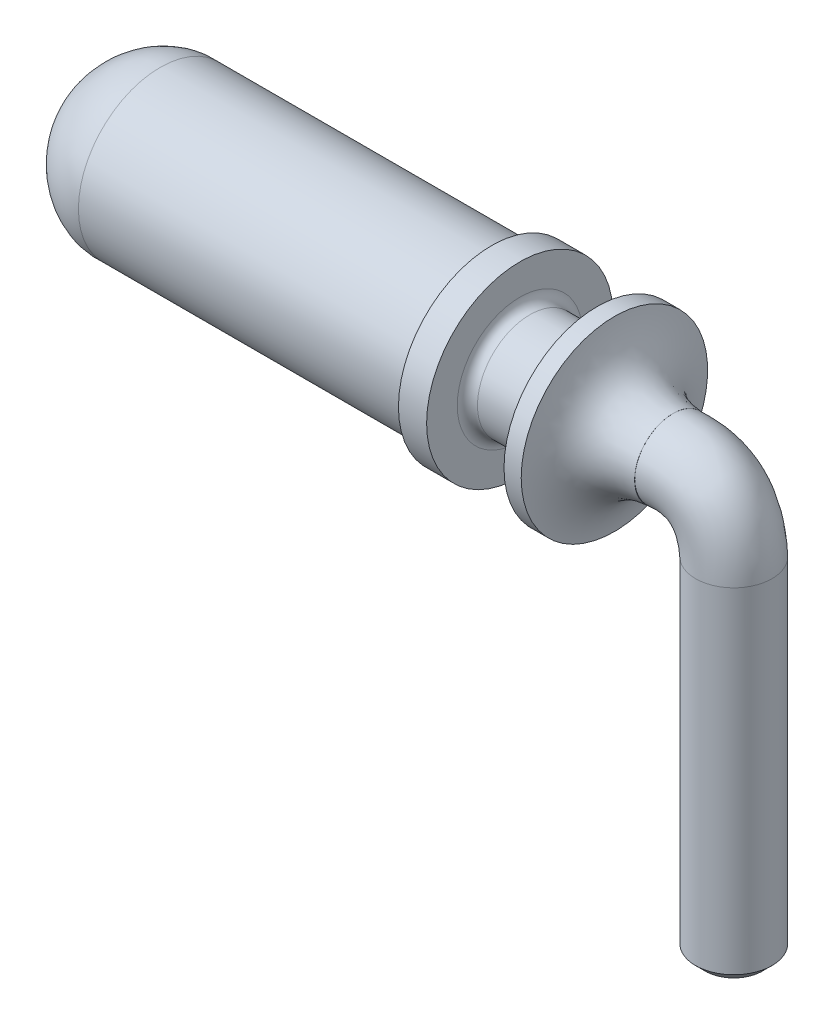
SolidWorks part; units mm, degrees
ref_plane "Front Plane" through (0, 0, 0) normal (0, 0, 1) x (1, 0, 0)
ref_plane "Top Plane" through (0, 0, 0) normal (0, 1, 0) x (1, 0, 0)
ref_plane "Right Plane" through (0, 0, 0) normal (1, 0, 0) x (0, 0, -1)
sketch "Sketch1" plane through (0, 0, 0) normal (0, 0, 1) x (1, 0, 0)
  line L0 (1.6261, 4.9868) -> (10.9215, 4.9868)
  line L1 (10.9215, 4.9868) -> (10.9215, 5.5888)
  line L2 (2.8612, 6.273) -> (8.0721, 6.273)
  line L3 (8.0721, 6.273) -> (8.0721, 6.4526)
  line L4 (8.0721, 6.4526) -> (8.5152, 6.4526)
  line L5 (8.5152, 6.4526) -> (8.5152, 5.9706)
  line L6 (8.6739, 5.8119) -> (9.5851, 5.8119)
  line L7 (9.732, 5.9589) -> (9.732, 6.4526)
  line L8 (9.732, 6.4526) -> (10.0024, 6.4526)
  arc A0 (8.5152, 5.9706) -> (8.6739, 5.8119) centre (8.6739, 5.9706) ccw
  arc A1 (9.5851, 5.8119) -> (9.732, 5.9589) centre (9.5851, 5.9589) ccw
  spline S0 degree 3 poles (1.6261, 4.9868) (1.5688, 5.6475) (2.2109, 6.321) (2.8612, 6.273) knots 0 0 0 0 1 1 1 1
  spline S1 degree 2 poles (10.0024, 6.4526) (10.1136, 5.6374) (10.9215, 5.5888) knots 0 0 0 1 1 1
  point P18 (10.9195, 5.5405)
  point P19 (10.9231, 5.6251)
  point P20 (10.9215, 5.5888)
revolve "Revolve1" add sketch "Sketch1" angle 360 about L0
sketch "Sketch2" plane through (0, 0, 0) normal (0, 0, 1) x (1, 0, 0)
  line L0 (11.8789, 4.1182) -> (11.8789, 0)
  line L1 (11.8789, 0) -> (11.8789, -1.3)
  line L2 (10.5466, 0) -> (13.6995, 0) construction
  line L3 (11.8789, 4.1182) -> (12.4789, 4.1182)
  line L4 (12.4789, 4.1182) -> (12.4789, -1.3)
  line L5 (12.4789, -1.3) -> (11.8789, -1.3)
  dimension "D1" = 1.3
  dimension "D2" = 0.6
revolve "Revolve2" add sketch "Sketch2" angle 360 about L0
sketch "Sketch3" plane through (0, 0, 0) normal (0, 0, 1) x (1, 0, 0)
  spline S0 degree 2 poles (10.9215, 4.9868) (11.8223, 5.0663) (11.8789, 4.1182) knots 0 0 0 1 1 1
sketch "Sketch10" plane through (0, 4.1182, 0) normal (0, 1, 0) x (1, 0, 0)
  circle A1 centre (11.8789, 0) radius 0.6
  circle A2 centre (11.8789, 0) radius 0.6
  dimension "D1" = 0
sweep "Sweep1" add profiles "Sketch10" path "Sketch3"
chamfer "Chamfer1" distance 0.15 angle 45 1 edges at (11.8789, -1.3, 0.6)
